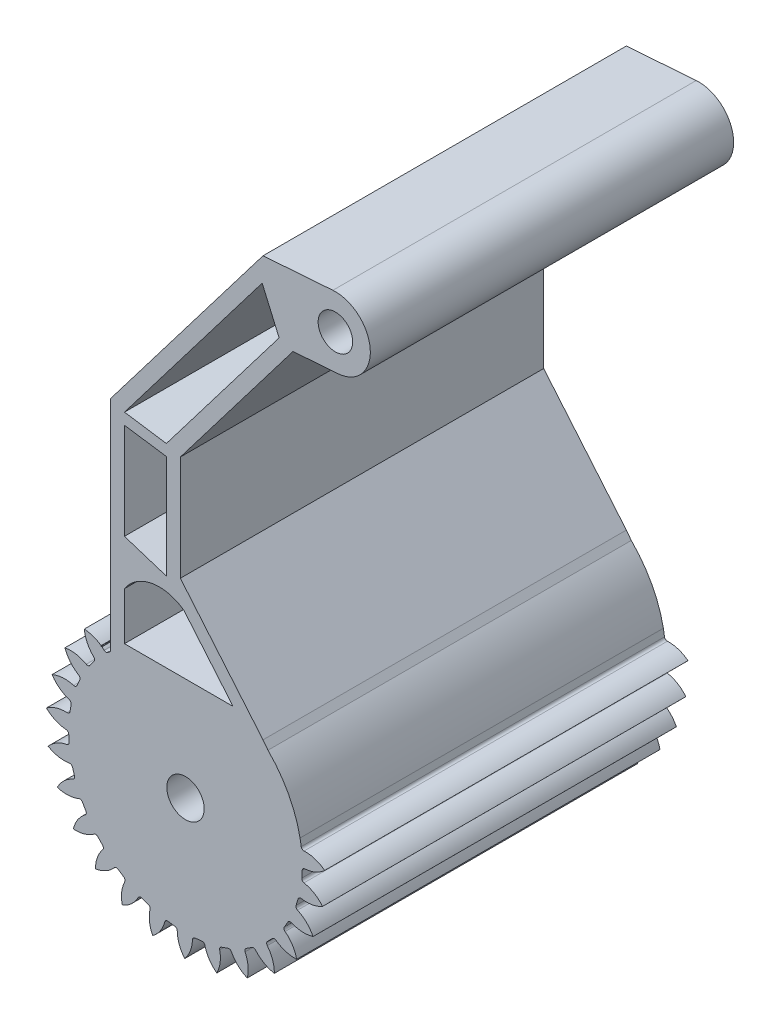
SolidWorks part; units mm, degrees
material "ABS"
ref_plane "Front Plane" through (0, 0, 0) normal (0, 0, 1) x (1, 0, 0)
ref_plane "Top Plane" through (0, 0, 0) normal (0, 1, 0) x (1, 0, 0)
ref_plane "Right Plane" through (0, 0, 0) normal (1, 0, 0) x (0, 0, -1)
sketch "Sketch1" plane through (0, 0, 0) normal (0, 0, 1) x (1, 0, 0)
  circle A0 centre (0, 0) radius 10.625
  circle A1 centre (0, 0) radius 11.475
  circle A2 centre (0, 0) radius 12.665
  dimension "D1" = 21.25
  dimension "D2" = 22.95
  dimension "D4" = 25.33
  dimension "D3" = 2.04
  dimension "D5" = 1.19
extrude "Boss-Extrude1" add sketch "Sketch1" along normal mid plane 33.02 contours A2
sketch "Sketch3" plane through (0, 0, 0) normal (0, 0, 1) x (1, 0, 0)
  line L0 (0, 0) -> (0, 31.9299) construction
  line L1 (-0.7205, 11.4524) -> (0.7205, 11.4524) construction
  line L2 (-0.5496, 10.6108) -> (0, 0) construction
  line L3 (0, 9.4727) -> (-7.4091, 29.8291) construction
  line L4 (-0.5496, 10.6108) -> (0.5496, 10.6108)
  line L5 (0, 0) -> (4.4013, 34.8396) construction
  line L6 (0.7205, 11.4524) -> (2.1502, 11.2717) construction
  arc A0 (-0.5496, 10.6108) -> (-3.0161, 13.328) centre (-3.4447, 10.4608) ccw
  arc A1 (0.5496, 10.6108) -> (3.0161, 13.328) centre (3.4447, 10.4608) cw
  circle A2 centre (0, 0) radius 10.625 construction
  circle A4 centre (0, 0) radius 11.475 construction
  circle A5 centre (0, 0) radius 13.665
  arc A6 (3.0161, 13.328) -> (-3.0161, 13.328) centre (0, 0) ccw
  dimension "D2" = 20
  dimension "D3" = 7.2
  dimension "D1" = 1
extrude "Cut-Extrude1" cut sketch "Sketch3" against normal through all both and the other way through all
fillet "Fillet1" radius 0.255 2 edges at (0.5496, 10.6108, 0) (-0.5496, 10.6108, 0)
pattern_circular "CirPattern1" count 25 every 13.31 about axis through (0, 0, 16.51) along (0, 0, 1) skipping 1, 2, 22, 23, 24 of "Fillet1", "Cut-Extrude1"
sketch "Sketch4" plane through (0, 0, 16.51) normal (0, 0, 1) x (1, 0, 0)
  point P0 (0, 0)
hole_wizard "M3 Clearance Hole1" positions "Sketch5" profile "Sketch6" hole size "M3" standard "ANSI Metric" end condition through all
sketch "Sketch5" plane through (0, 0, 16.51) normal (0, 0, 1) x (1, 0, 0)
  point P0 (0, 0)
sketch "Sketch6" plane through (0, 0, 16.51) normal (1, 0, 0) x (0, -1, 0)
  line L0 (0, 0) -> (0, 33.02)
  line L1 (0, 33.02) -> (1.7, 33.02)
  line L2 (1.7, 33.02) -> (1.7, 0)
  line L5 (1.7, 0) -> (0, 0)
  line L11 (0, -6.35) -> (0, 107.95) construction
  dimension "Thru Hole Dia." = 3.4
  dimension "Thru Hole Depth" = 33.02
sketch "Sketch7" plane through (0, 0, 16.51) normal (0, 0, 1) x (1, 0, 0)
  line L1 (-7.669, 8.1096) -> (7.764, 8.1096)
  line L2 (-7.669, 8.1096) -> (-7.669, 13.4958)
  line L3 (-7.669, 13.4958) -> (7.764, 13.4958)
  line L4 (7.764, 8.1096) -> (7.764, 13.4958)
  dimension "D1" = 8.1096
extrude "Cut-Extrude2" cut sketch "Sketch7" against normal through all
sketch "Sketch8" plane through (0, 0, 0) normal (0, 0, 1) x (1, 0, 0)
  line L1 (-6.8174, 8.1096) -> (-6.8174, 28.0324)
  line L2 (-6.8174, 28.0324) -> (7.0451, 46.2096)
  line L3 (7.0451, 46.2096) -> (13.3951, 46.6677)
  line L5 (13.8521, 40.3342) -> (9.7724, 40.0398)
  line L6 (9.7724, 40.0398) -> (-0.4674, 26.613)
  line L7 (-0.4674, 26.613) -> (-0.4674, 17.0688)
  line L8 (-0.4674, 17.0688) -> (7.0451, 8.1096)
  line L9 (7.0451, 8.1096) -> (7.0451, 60.6555) construction
  line L11 (0.9945, 8.1096) -> (11.1542, -0.1084) construction
  line L12 (11.1542, -0.1084) -> (7.0451, 8.1096) construction
  line L13 (-7.669, 8.1096) -> (-7.5896, 8.1096) construction
  line L23 (-5.5474, 9.3796) -> (-5.5474, 13.7111)
  line L24 (-5.5474, 27.6034) -> (6.9689, 44.0153)
  line L27 (8.5091, 40.4778) -> (-1.7374, 27.042)
  line L28 (-1.7374, 26.0151) -> (-1.7374, 16.6068)
  line L29 (-0.1351, 14.6959) -> (4.3228, 9.3796)
  line L30 (0.9945, 9.3796) -> (4.3228, 9.3796)
  line L31 (0.9945, 9.3796) -> (-5.5474, 9.3796)
  line L32 (-5.5474, 27.6034) -> (-1.7374, 27.042)
  line L33 (-5.5474, 26.5764) -> (-1.7374, 26.0151)
  line L35 (6.9689, 44.0153) -> (8.5091, 40.4778)
  line L36 (-1.7374, 16.6068) -> (-5.5474, 17.8308)
  line L37 (-5.5474, 27.6034) -> (7.7077, 44.9841) construction
  line L38 (9.1098, 41.2653) -> (-1.7374, 27.042) construction
  line L39 (13.7607, 41.6009) -> (9.1098, 41.2653) construction
  line L40 (7.7077, 44.9841) -> (13.4865, 45.401) construction
  line L41 (-1.7374, 27.042) -> (-1.7374, 16.6068) construction
  line L42 (-5.5474, 9.3796) -> (-5.5474, 27.6034) construction
  line L43 (-5.5474, 17.8308) -> (-5.5474, 26.5764)
  line L45 (-1.7374, 16.6068) -> (4.3228, 9.3796) construction
  line L55 (0.9945, 8.1096) -> (-6.8174, 8.1096) construction
  line L57 (0.9945, 8.1096) -> (7.0451, 8.1096) construction
  line L59 (-6.8174, 8.1096) -> (7.0451, 8.1096)
  arc A0 (13.3951, 46.6677) -> (13.8521, 40.3342) centre (13.6236, 43.501) cw
  arc A3 (-5.5474, 13.7111) -> (-0.1351, 14.6959) centre (-2.3794, 11.6656) cw
  circle A4 centre (13.6236, 43.501) radius 1.57
  arc A5 (13.4865, 45.401) -> (13.7607, 41.6009) centre (13.6236, 43.501) cw construction
  point P33 (0, 0)
  point P37 (-6.8174, 8.1096)
  dimension "D7" = 3.175
  dimension "D13" = 2.286
  dimension "D16" = 3.14
  dimension "D2" = 22.86
  dimension "D3" = 6.35
  dimension "D4" = 6.35
  dimension "D5" = 6.35
  dimension "D6" = 31.9303
  dimension "D8" = 6.0506
  dimension "D9" = 2.7272
  dimension "D12" = 1.27
  dimension "D14" = 1.016
  dimension "D17" = 72.19
extrude "claw part" add sketch "Sketch8" along normal through all and the other way through all
sketch "Sketch9" plane through (0, 0, 16.51) normal (0, 0, 1) x (1, 0, 0)
  line L2 (7.0451, 8.1096) -> (7.4969, 7.5157)
  line L3 (7.0451, 8.1096) -> (7.7607, 10.8129)
  line L4 (7.7607, 10.8129) -> (13.3562, 4.0736)
  line L5 (13.3562, 4.0736) -> (10.4807, 1.6862)
  arc A0 (10.4807, 1.6862) -> (7.4969, 7.5157) centre (0, 0) ccw
extrude "Cut-Extrude3" cut sketch "Sketch9" against normal through all
sketch "Sketch11" plane through (0, 0, 16.51) normal (0, 0, 1) x (1, 0, 0)
  circle A0 centre (0, 0) radius 12.665
equation "\"module\"= 0.85mm"
equation "\"number of teeth\"= 25"
equation "\"D1@Sketch1\"=\"module\"*\"number of teeth\""
equation "\"D2@Sketch1\"=(\"number of teeth\"+2)*(\"module\")"
equation "\"D3@Sketch1\"=\"module\"*if(\"module\"=>1.25,2.25,2.4)"
equation "\"D3@Sketch3\"=180/\"number of teeth\""
equation "\"D1@Fillet1\"=.3*\"module\""
equation "\"D1@CirPattern1\"=\"number of teeth\""
